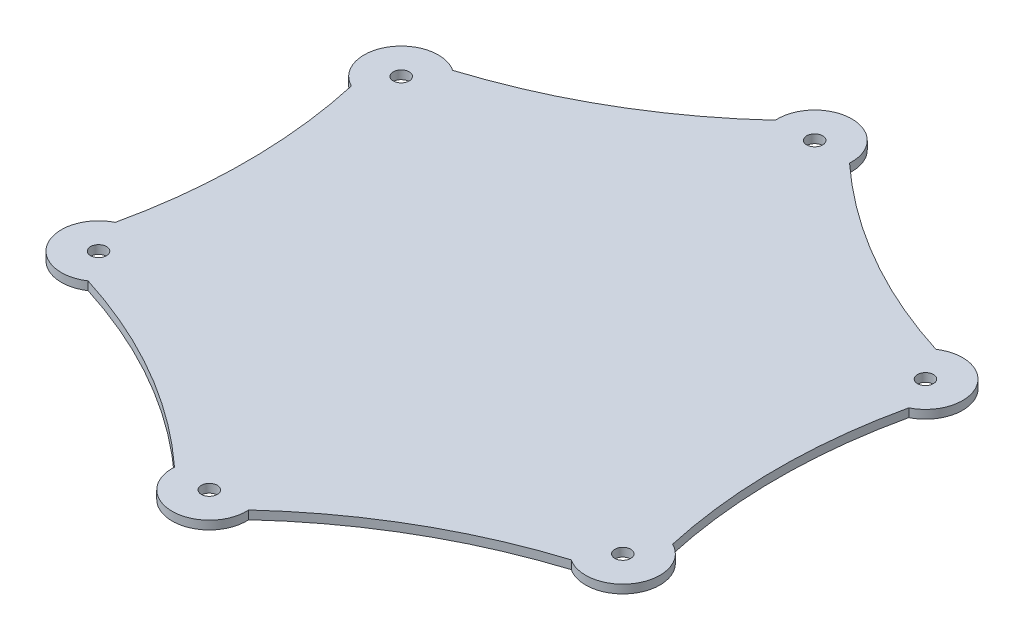
SolidWorks part; units mm, degrees
material "Fibra de Vidro A"
ref_plane "Plano frontal" through (0, 0, 0) normal (0, 0, 1) x (1, 0, 0)
ref_plane "Plano superior" through (0, 0, 0) normal (0, 1, 0) x (1, 0, 0)
ref_plane "Plano direito" through (0, 0, 0) normal (1, 0, 0) x (0, 0, -1)
sketch "Esboço1" plane through (0, 0, 0) normal (0, 1, 0) x (1, 0, 0)
  circle A0 centre (0, 0) radius 50 construction
  circle A1 centre (0, 0) radius 64 construction
  circle A2 centre (0, 57) radius 5.85 construction
  circle A3 centre (0, 57) radius 1.5
  circle A4 centre (49.3634, 28.5) radius 5.85 construction
  circle A5 centre (49.3634, 28.5) radius 1.5
  circle A6 centre (49.3634, -28.5) radius 5.85 construction
  circle A7 centre (49.3634, -28.5) radius 1.5
  circle A8 centre (0, -57) radius 5.85 construction
  circle A9 centre (0, -57) radius 1.5
  circle A10 centre (-49.3634, -28.5) radius 5.85 construction
  circle A11 centre (-49.3634, -28.5) radius 1.5
  circle A12 centre (-49.3634, 28.5) radius 5.85 construction
  circle A13 centre (-49.3634, 28.5) radius 1.5
  arc A14 (6.9868, 56.5702) -> (-6.9868, 56.5702) centre (0, 57) ccw
  arc A15 (-45.4978, 34.3358) -> (-52.4846, 22.2343) centre (-49.3634, 28.5) ccw
  circle A16 centre (0, 0) radius 57 construction
  arc A17 (-45.4978, 34.3358) -> (-6.9868, 56.5702) centre (-75.8804, 131.4288) ccw
  arc A18 (6.9868, 56.5702) -> (45.4978, 34.3358) centre (75.8804, 131.4288) ccw
  arc A19 (52.4846, 22.2343) -> (45.4978, 34.3358) centre (49.3634, 28.5) ccw
  arc A20 (52.4846, 22.2343) -> (52.4846, -22.2343) centre (151.7609, 0) ccw
  arc A21 (45.4978, -34.3358) -> (52.4846, -22.2343) centre (49.3634, -28.5) ccw
  arc A22 (45.4978, -34.3358) -> (6.9868, -56.5702) centre (75.8804, -131.4288) ccw
  arc A23 (-6.9868, -56.5702) -> (6.9868, -56.5702) centre (0, -57) ccw
  arc A24 (-6.9868, -56.5702) -> (-45.4978, -34.3358) centre (-75.8804, -131.4288) ccw
  arc A25 (-52.4846, -22.2343) -> (-45.4978, -34.3358) centre (-49.3634, -28.5) ccw
  arc A26 (-52.4846, -22.2343) -> (-52.4846, 22.2343) centre (-151.7609, 0) ccw
  arc A27 (-45.4978, 34.3358) -> (-52.4846, 22.2343) centre (-49.3634, 28.5) ccw
  dimension "D1" = 128
  dimension "D2" = 11.7
  dimension "D3" = 100
  dimension "D4" = 3
  dimension "D5" = 57
  dimension "D6" = 49.3634
  dimension "D7" = 6
  dimension "D8" = 114
  dimension "D9" = 101.7356
  dimension "D10" = 57
  dimension "D11" = 6
extrude "Ressalto-extrusão1" add sketch "Esboço1" along normal blind 1.6 contours A26 A25 A24 A23 A22 A21 A20 A19 A18 A14 A17 A15 A13 A11 A9 A7 A5 A3
